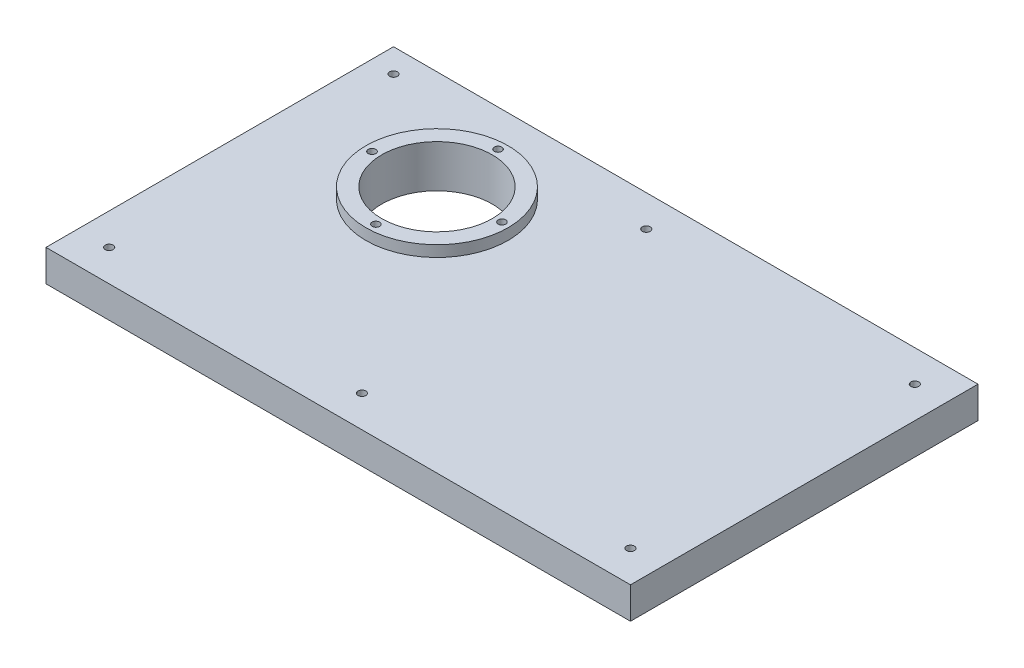
SolidWorks part; units mm, degrees
material "3.0515 (EN-AW 3103)"
ref_plane "前视" through (0, 0, 0) normal (0, 0, 1) x (1, 0, 0)
ref_plane "上视" through (0, 0, 0) normal (0, 1, 0) x (1, 0, 0)
ref_plane "右视" through (0, 0, 0) normal (1, 0, 0) x (0, 0, -1)
sketch "草图2" plane through (0, 0, 0) normal (0, 1, 0) x (1, 0, 0)
  line L1 (0, 18.9896) -> (370, 18.9896)
  line L2 (0, 18.9896) -> (0, -201.0104)
  line L3 (0, -201.0104) -> (370, -201.0104)
  line L4 (370, 18.9896) -> (370, -201.0104)
  dimension "D1" = 370
  dimension "D2" = 220
extrude "凸台-拉伸1" add sketch "草图2" along normal blind 20
sketch "草图3" plane through (0, 20, 0) normal (0, 1, 0) x (1, 0, 0)
  line L1 (0, 18.9896) -> (0, -201.0104) construction
  line L2 (370, 18.9896) -> (0, 18.9896) construction
  line L3 (370, -201.0104) -> (370, 18.9896) construction
  line L4 (0, -201.0104) -> (370, -201.0104) construction
  circle A0 centre (15, 3.9896) radius 2.5
  circle A1 centre (20, -181.0104) radius 2.5
  circle A2 centre (350, -1.0104) radius 2.5
  circle A3 centre (350, -181.0104) radius 2.5
  circle A4 centre (180, -1.0104) radius 2.5
  circle A5 centre (180, -181.0104) radius 2.5
  dimension "D1" = 5
  dimension "D3" = 15
  dimension "D4" = 5
  dimension "D6" = 5
  dimension "D8" = 20
  dimension "D9" = 5
  dimension "D10" = 20
  dimension "D11" = 20
  dimension "D12" = 5
  dimension "D13" = 20
  dimension "D14" = 5
  dimension "D15" = 20
  dimension "D16" = 20
  dimension "D17" = 170
  dimension "D18" = 170
  dimension "D2" = 15
  dimension "D5" = 20
  dimension "D7" = 20
extrude "切除-拉伸1" cut sketch "草图3" against normal blind 20
sketch "草图4" plane through (0, 20, 0) normal (0, 1, 0) x (1, 0, 0)
  line L0 (370, 18.9896) -> (0, 18.9896) construction
  circle A0 centre (97.5031, -51.0104) radius 35
  dimension "D1" = 70
  dimension "D2" = 70
extrude "切除-拉伸2" cut sketch "草图4" against normal up to next contours A0
sketch "草图5" plane through (0, 20, 0) normal (0, 1, 0) x (1, 0, 0)
  circle A0 centre (97.5031, -51.0104) radius 45
  dimension "D1" = 90
extrude "凸台-拉伸2" add sketch "草图5" along normal blind 7 contours A0
sketch "草图6" plane through (0, 27, 0) normal (0, 1, 0) x (1, 0, 0)
  circle A0 centre (97.5031, -51.0104) radius 35
  dimension "D1" = 70
extrude "切除-拉伸3" cut sketch "草图6" against normal blind 39 contours A0
sketch "草图7" plane through (0, 27, 0) normal (0, 1, 0) x (1, 0, 0)
  circle A0 centre (96.2737, -11.1155) radius 2.3779
  circle A1 centre (137.398, -49.781) radius 2.3779
  circle A2 centre (98.7325, -90.9052) radius 2.3779
  circle A3 centre (57.6083, -52.2398) radius 2.3779
  point P11 (97.5031, -51.0104)
  dimension "D1" = 4.7557
  dimension "D2" = 4
extrude "切除-拉伸4" cut sketch "草图7" against normal blind 39
sketch "草图9" plane through (0, 0, 0) normal (0, -1, 0) x (-1, 0, 0)
  line L1 (-9.0282, -196.1697) -> (-360.4284, -196.1697)
  line L2 (-4.0282, -191.1697) -> (-4.0282, 9.6924)
  line L3 (-9.0282, 14.6924) -> (-360.4284, 14.6924)
  line L4 (-365.4284, -191.1697) -> (-365.4284, 9.6924)
  line L5 (-12.8324, -191.2786) -> (-355.5372, -191.2786)
  line L6 (-7.8324, -186.2786) -> (-7.8324, 4.2578)
  line L7 (-12.8324, 9.2578) -> (-355.5372, 9.2578)
  line L8 (-360.5372, -186.2786) -> (-360.5372, 4.2578)
  arc A0 (-360.4284, -196.1697) -> (-365.4284, -191.1697) centre (-360.4284, -191.1697) cw
  arc A1 (-355.5372, -191.2786) -> (-360.5372, -186.2786) centre (-355.5372, -186.2786) cw
  arc A2 (-365.4284, 9.6924) -> (-360.4284, 14.6924) centre (-360.4284, 9.6924) cw
  arc A3 (-360.5372, 4.2578) -> (-355.5372, 9.2578) centre (-355.5372, 4.2578) cw
  arc A4 (-4.0282, 9.6924) -> (-9.0282, 14.6924) centre (-9.0282, 9.6924) ccw
  arc A5 (-7.8324, 4.2578) -> (-12.8324, 9.2578) centre (-12.8324, 4.2578) ccw
  arc A6 (-12.8324, -191.2786) -> (-7.8324, -186.2786) centre (-12.8324, -186.2786) ccw
  arc A7 (-4.0282, -191.1697) -> (-9.0282, -196.1697) centre (-9.0282, -191.1697) cw
  dimension "D1" = 5
extrude "切除-拉伸5" cut sketch "草图9" against normal blind 5
